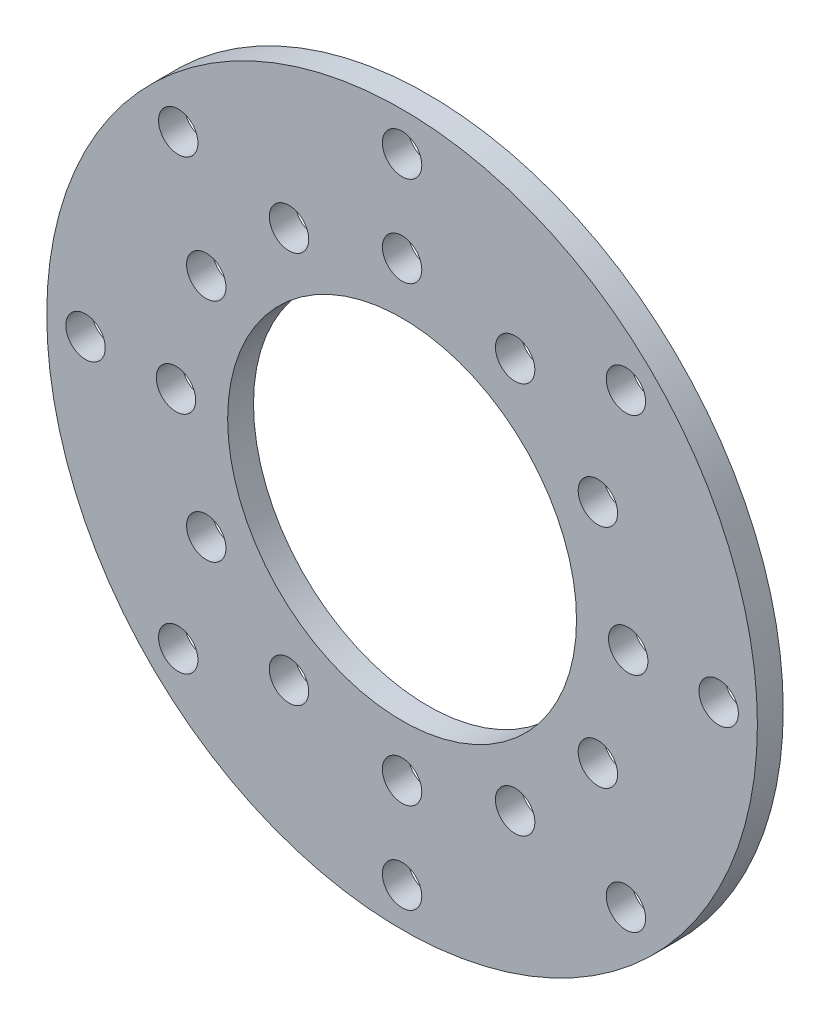
SolidWorks part; units mm, degrees
material "Thornel Mat VMA"
ref_plane "前视基准面" through (0, 0, 0) normal (0, 0, 1) x (1, 0, 0)
ref_plane "上视基准面" through (0, 0, 0) normal (0, 1, 0) x (1, 0, 0)
ref_plane "右视基准面" through (0, 0, 0) normal (1, 0, 0) x (0, 0, -1)
sketch "草图1" plane through (0, 0, 0) normal (0, 0, 1) x (1, 0, 0)
  circle A0 centre (0, 0) radius 13.5
  circle A1 centre (0, 0) radius 21 construction
  circle A2 centre (0, 0) radius 27.5
  dimension "D1" = 27
  dimension "D2" = 42
  dimension "D3" = 6.5
extrude "凸台-拉伸1" add sketch "草图1" along normal blind 2
sketch "草图2" plane through (0, 0, 2) normal (0, 0, 1) x (1, 0, 0)
  circle A0 centre (0, 0) radius 17.5 construction
  circle A1 centre (0, 17.5) radius 1.525
  circle A2 centre (8.75, 15.1554) radius 1.525
  circle A3 centre (15.1554, 8.75) radius 1.525
  circle A4 centre (17.5, 0) radius 1.525
  circle A5 centre (15.1554, -8.75) radius 1.525
  circle A6 centre (8.75, -15.1554) radius 1.525
  circle A7 centre (0, -17.5) radius 1.525
  circle A8 centre (-8.75, -15.1554) radius 1.525
  circle A9 centre (-15.1554, -8.75) radius 1.525
  circle A10 centre (-17.5, 0) radius 1.525
  circle A11 centre (-15.1554, 8.75) radius 1.525
  circle A12 centre (-8.75, 15.1554) radius 1.525
  point P5 (0.237, -22.7923)
  point P6 (0, 0)
  point P29 (0, 0)
  dimension "D1" = 35
  dimension "D2" = 3.05
  dimension "D3" = 12
extrude "切除-拉伸1" cut sketch "草图2" against normal blind 2
sketch "草图3" plane through (0, 0, 2) normal (0, 0, 1) x (1, 0, 0)
  circle A0 centre (0, 0) radius 24.5 construction
  circle A1 centre (0, 0) radius 27.5 construction
  circle A2 centre (0, 24.5) radius 1.525
  circle A3 centre (17.3241, 17.3241) radius 1.525
  circle A4 centre (24.5, 0) radius 1.525
  circle A5 centre (17.3241, -17.3241) radius 1.525
  circle A6 centre (0, -24.5) radius 1.525
  circle A7 centre (-17.3241, -17.3241) radius 1.525
  circle A8 centre (-24.5, 0) radius 1.525
  circle A9 centre (-17.3241, 17.3241) radius 1.525
  point P7 (-16.7808, -25.6454)
  point P8 (0, 0)
  point P31 (0, 0)
  dimension "D1" = 3
  dimension "D2" = 3.05
  dimension "D3" = 8
extrude "切除-拉伸2" cut sketch "草图3" against normal blind 2
